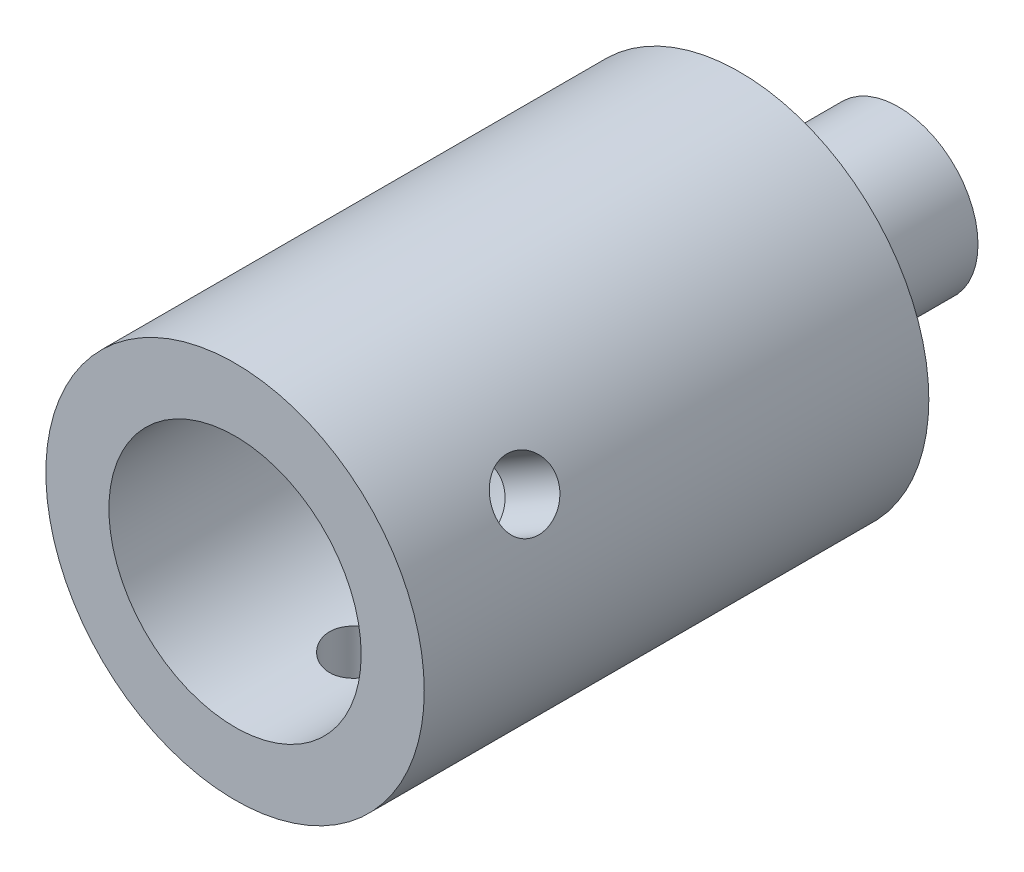
SolidWorks part; units mm, degrees
material "1060 Alloy"
ref_plane "Front Plane" through (0, 0, 0) normal (0, 0, 1) x (1, 0, 0)
ref_plane "Top Plane" through (0, 0, 0) normal (0, 1, 0) x (1, 0, 0)
ref_plane "Right Plane" through (0, 0, 0) normal (1, 0, 0) x (0, 0, -1)
sketch "Sketch1" plane through (0, 0, 0) normal (0, 0, 1) x (1, 0, 0)
  circle A0 centre (0, 0) radius 4
  dimension "D1" = 8
extrude "Boss-Extrude1" add sketch "Sketch1" along normal blind 7
sketch "Sketch2" plane through (0, 0, 7) normal (0, 0, 1) x (1, 0, 0)
  circle A0 centre (0, 0) radius 5.5
  dimension "D1" = 11
extrude "Boss-Extrude2" add sketch "Sketch2" along normal blind 1
sketch "Sketch3" plane through (0, 0, 8) normal (0, 0, 1) x (1, 0, 0)
  circle A0 centre (0, 0) radius 9.525
  dimension "D1" = 19.05
extrude "Boss-Extrude3" add sketch "Sketch3" along normal blind 25.4
sketch "Sketch4" plane through (0, 0, 33.4) normal (0, 0, 1) x (1, 0, 0)
  circle A0 centre (0, 0) radius 6.35
  dimension "D1" = 12.7
extrude "Cut-Extrude1" cut sketch "Sketch4" against normal blind 19.05
sketch "Sketch5" plane through (0, 0, 0) normal (0, 1, 0) x (1, 0, 0)
  line L0 (-9.525, -33.4) -> (9.525, -33.4) construction
  circle A0 centre (0, -27.05) radius 1.5875
  dimension "D1" = 3.175
  dimension "D2" = 6.35
extrude "Cut-Extrude2" cut sketch "Sketch5" against normal blind 25.4
pattern_circular "CirPattern1" count 3 every 120 about axis through (0, 0, 33.4) along (0, 0, -1) of "Cut-Extrude2"
